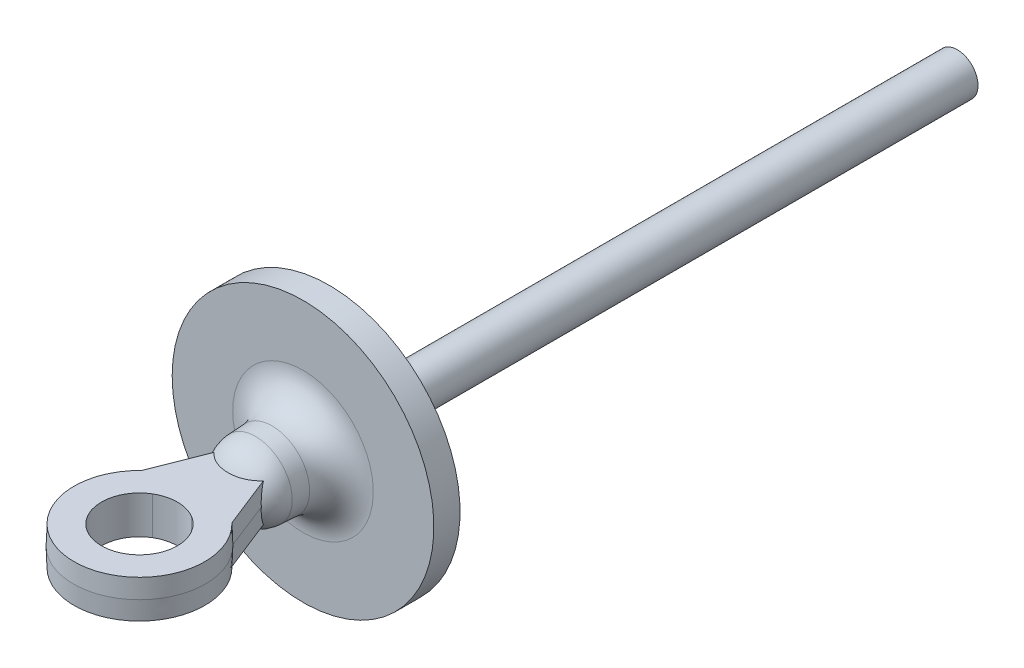
SolidWorks part; units mm, degrees
material "Cast Carbon Steel"
ref_plane "Plane1" through (0, 0, 0) normal (0, 0, 1) x (1, 0, 0)
ref_plane "Plane2" through (0, 0, 0) normal (0, 1, 0) x (1, 0, 0)
ref_plane "Plane3" through (0, 0, 0) normal (1, 0, 0) x (0, 0, -1)
other "Configuration Table"
sketch "Sketch1" plane through (0, 0, 0) normal (0, 0, 1) x (1, 0, 0)
  circle A0 centre (0, 0) radius 3
  dimension "D1" = 6
extrude "Base-Extrude" add sketch "Sketch1" along normal blind 6 draft 3
fillet "Fillet1" radius 2.5 1 edges at (2.6856, 0, 6)
sketch "Sketch2" plane through (0, 0, 0) normal (0, 1, 0) x (1, 0, 0)
  line L0 (3.4959, -8.8557) -> (0, 0)
  line L1 (0, 0) -> (-3.4959, -8.8557)
  arc A0 (-3.4959, -8.8557) -> (3.4959, -8.8557) centre (0, -12.5) ccw
  dimension "D1" = 10.1
  dimension "D2" = 12.5
extrude "Boss-Extrude1" add sketch "Sketch2" along normal mid plane 2.9 draft 2
sketch "Sketch3" plane through (0, -1.45, 0) normal (0, -1, 0) x (1, 0, 0)
  circle A0 centre (0, 12.5) radius 2.9
  arc A1 (3.4529, 8.8846) -> (-3.4529, 8.8846) centre (0, 12.5) ccw construction
  dimension "D1" = 5.8
extrude "Cut-Extrude1" cut sketch "Sketch3" against normal through all
sketch "Sketch4" plane through (0, 0, 0) normal (0, 0, -1) x (-1, 0, 0)
  circle A0 centre (0, 0) radius 1.585
  dimension "D1" = 3.17
extrude "Boss-Extrude2" add sketch "Sketch4" along normal blind 50
sketch "Sketch5" plane through (0, 0, 0) normal (0, 0, -1) x (-1, 0, 0)
  circle A0 centre (0, 0) radius 10
  circle A1 centre (0, 0) radius 1.585 construction
  circle A2 centre (0, 0) radius 1.585
  dimension "D1" = 20
extrude "Boss-Extrude3" add sketch "Sketch5" along normal blind 1
sketch "Sketch11" plane through (0, 0, -1) normal (0, 0, -1) x (-1, 0, 0)
  circle A0 centre (0, 0) radius 9
  circle A1 centre (0, 0) radius 10
  circle A2 centre (0, 0) radius 10
  dimension "D1" = 0
  dimension "D2" = 1
extrude "Extrude1" add sketch "Sketch11" along normal blind 1
fillet "Fillet5" radius 2.5 1 edges at (-3, 0, 0)
sketch "Sketch9" plane through (0, 0, 0) normal (0, 0, 1) x (1, 0, 0)
  line L0 (0, 10.738) -> (0, -10.9867) construction
  line L1 (1.884, 1.45) -> (-1.884, 1.45) construction
  line L2 (-1.5, 1.45) -> (1.5, 1.45)
  line L3 (-1.5, 1.45) -> (-1.5, -1.45)
  line L4 (-1.5, -1.45) -> (1.5, -1.45)
  line L5 (1.5, 1.45) -> (1.5, -1.45)
  line L6 (-1.884, -1.45) -> (1.884, -1.45) construction
  circle A1 centre (0, 0) radius 10
  circle A2 centre (0, 0) radius 10 construction
  dimension "D2" = 3
  dimension "D3" = 1.5
  dimension "D1" = 0
split line "Split Line2"
ref_point "Point1"
fillet "Fillet6" radius 2 1 edges at (-1.585, 0, -1)
